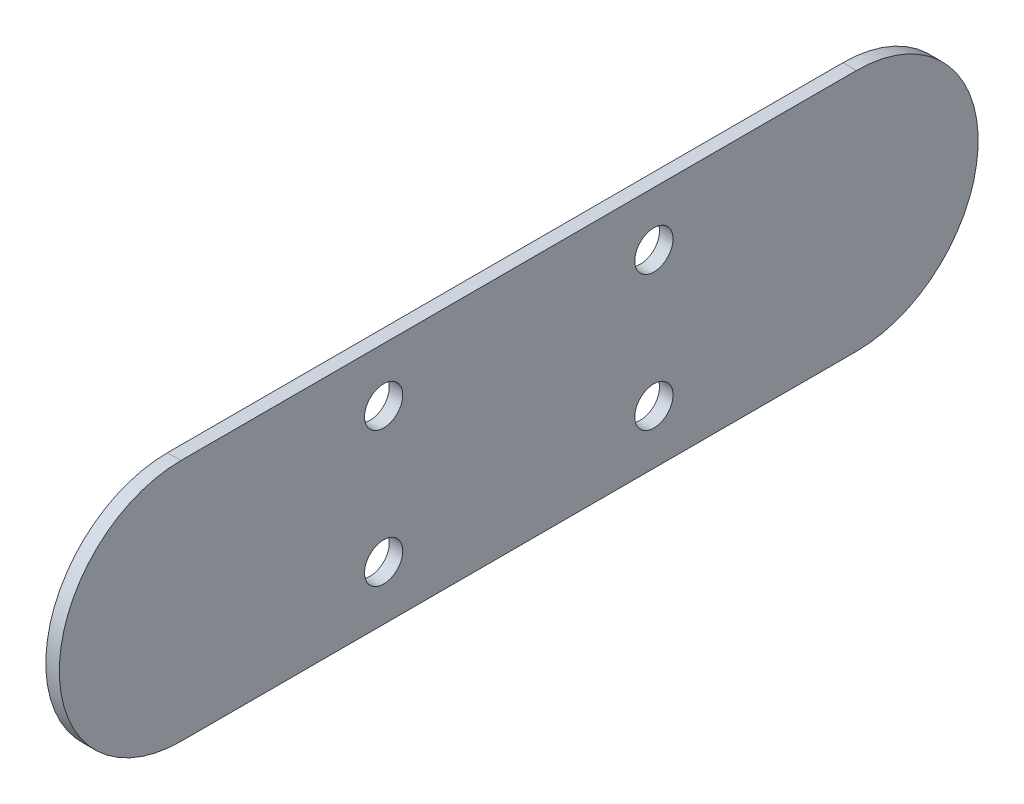
SolidWorks part; units mm, degrees
material "6061 Alloy"
ref_plane "Front Plane" through (0, 0, 0) normal (0, 0, 1) x (1, 0, 0)
ref_plane "Top Plane" through (0, 0, 0) normal (0, 1, 0) x (1, 0, 0)
ref_plane "Right Plane" through (0, 0, 0) normal (1, 0, 0) x (0, 0, -1)
sketch "Sketch2" plane through (0, 0, 0) normal (1, 0, 0) x (0, 0, -1)
  line L0 (39.6875, 0) -> (-39.6875, 0) construction
  line L1 (39.6875, -14.2875) -> (-39.6875, -14.2875)
  line L2 (39.6875, 14.2875) -> (-39.6875, 14.2875)
  arc A0 (39.6875, -14.2875) -> (39.6875, 14.2875) centre (39.6875, 0) ccw
  arc A1 (-39.6875, 14.2875) -> (-39.6875, -14.2875) centre (-39.6875, 0) ccw
  point P2 (0, 0)
  dimension "D2" = 28.575
  dimension "D1" = 79.375
extrude "Boss-Extrude1" add sketch "Sketch2" along normal blind 1.5875
sketch "Sketch3" plane through (1.5875, 0, 0) normal (1, 0, 0) x (0, 0, -1)
  line L1 (15.875, -7.9375) -> (-15.875, -7.9375)
  line L2 (15.875, -7.9375) -> (15.875, 7.9375)
  line L3 (15.875, 7.9375) -> (-15.875, 7.9375)
  line L4 (-15.875, -7.9375) -> (-15.875, 7.9375)
  line L5 (15.875, -7.9375) -> (-15.875, 7.9375) construction
  line L6 (15.875, 7.9375) -> (-15.875, -7.9375) construction
  point P0 (0, 0)
  dimension "D1" = 31.75
  dimension "D2" = 15.875
hole_wizard "#8 Clearance Hole1" positions "Sketch4" profile "Sketch5" hole size "#8" standard "ANSI Inch" end condition up to next
sketch "Sketch4" plane through (1.5875, 0, 0) normal (1, 0, 0) x (0, 0, -1)
  point P0 (-15.875, 7.9375)
  point P3 (-15.875, -7.9375)
  point P6 (15.875, -7.9375)
  point P9 (15.875, 7.9375)
sketch "Sketch5" plane through (1.5875, 7.9375, 15.875) normal (0, 1, 0) x (0, 0, -1)
  line L0 (0, 0) -> (0, 1.5875)
  line L1 (0, 1.5875) -> (2.2479, 1.5875)
  line L2 (2.2479, 1.5875) -> (2.2479, 0)
  line L5 (2.2479, 0) -> (0, 0)
  line L11 (0, -6.35) -> (0, 107.95) construction
  dimension "Thru Hole Dia." = 4.4958
  dimension "Thru Hole Depth" = 1.5875
